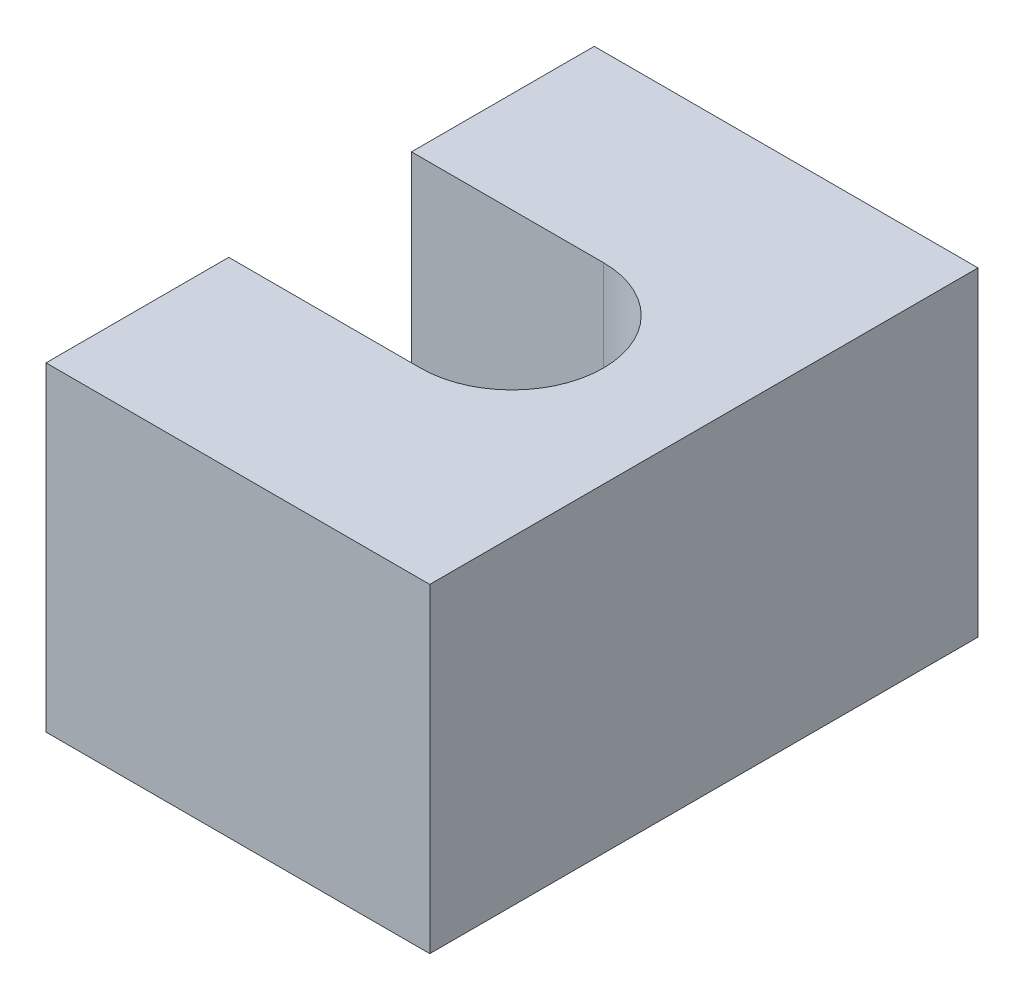
SolidWorks part; units mm, degrees
ref_plane "Front Plane" through (0, 0, 0) normal (0, 0, 1) x (1, 0, 0)
ref_plane "Top Plane" through (0, 0, 0) normal (0, 1, 0) x (1, 0, 0)
ref_plane "Right Plane" through (0, 0, 0) normal (1, 0, 0) x (0, 0, -1)
sketch "Sketch1" plane through (0, 0, 0) normal (0, 1, 0) x (1, 0, 0)
  line L1 (0, 0) -> (42, 0)
  line L2 (0, 0) -> (0, 60)
  line L3 (0, 60) -> (42, 60)
  line L4 (42, 0) -> (42, 60)
  dimension "D1" = 60
  dimension "D2" = 42
extrude "Boss-Extrude1" add sketch "Sketch1" along normal blind 10
sketch "Sketch2" plane through (0, 10, 0) normal (0, 1, 0) x (1, 0, 0)
  line L0 (0, 30) -> (42, 30) construction
  line L1 (0, 60) -> (0, 0) construction
  line L2 (42, 0) -> (42, 60) construction
  line L3 (0, 20) -> (21, 20)
  line L4 (0, 20) -> (0, 0)
  line L5 (0, 0) -> (42, 0)
  line L6 (42, 0) -> (42, 60)
  line L7 (0, 60) -> (42, 60)
  line L8 (0, 40) -> (0, 60)
  line L9 (0, 40) -> (21, 40)
  arc A0 (21, 20) -> (21, 40) centre (21, 30) ccw
  dimension "D2" = 10
  dimension "D3" = 21
  dimension "D1" = 20
extrude "Boss-Extrude2" add sketch "Sketch2" along normal blind 25
sketch "Sketch3" plane through (0, 0, 0) normal (-1, 0, 0) x (0, 0, 1)
  line L0 (-30, 10) -> (-30, 36.6037) construction
  line L1 (-40, 10) -> (-20, 10) construction
  line L3 (-20, 22.5) -> (0, 22.5) construction
  line L4 (-20, 35) -> (-20, 10) construction
  line L5 (0, 35) -> (0, 0) construction
  line L6 (-10, 35) -> (-10, 0) construction
  line L7 (-20, 35) -> (0, 35) construction
  line L8 (-60, 0) -> (0, 0) construction
  circle A0 centre (-10, 22.5) radius 4
  circle A1 centre (-50, 22.5) radius 4
  dimension "D1" = 8
extrude "Cut-Extrude1" cut sketch "Sketch3" against normal blind 15
sketch "Sketch4" plane through (0, 10, 0) normal (0, 1, 0) x (1, 0, 0)
  line L0 (0, 40) -> (0, 20) construction
  line L1 (0, 30) -> (56.7537, 30) construction
  circle A0 centre (20.85, 30) radius 2.5
  dimension "D1" = 5
  dimension "D2" = 20.85
extrude "Cut-Extrude2" cut sketch "Sketch4" against normal blind 15
